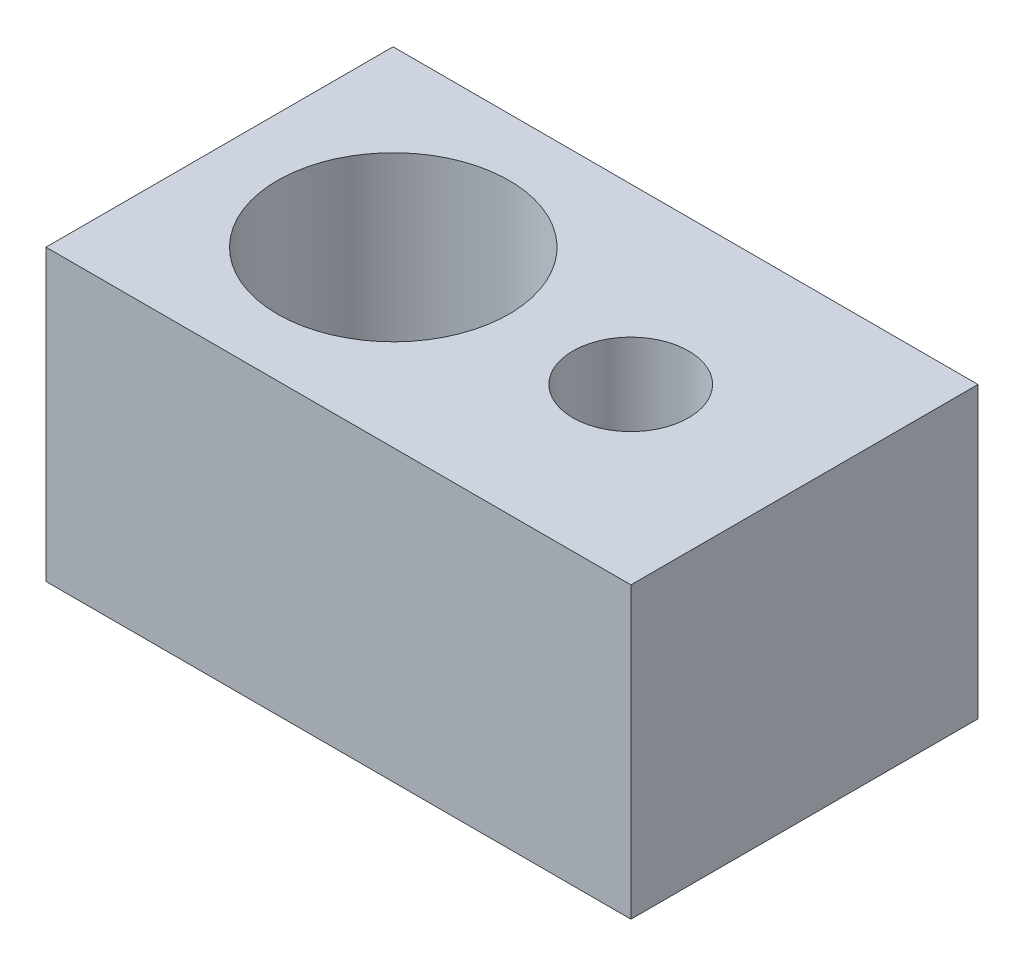
SolidWorks part; units mm, degrees
ref_plane "Front Plane" through (0, 0, 0) normal (0, 0, 1) x (1, 0, 0)
ref_plane "Top Plane" through (0, 0, 0) normal (0, 1, 0) x (1, 0, 0)
ref_plane "Right Plane" through (0, 0, 0) normal (1, 0, 0) x (0, 0, -1)
sketch "Sketch1" plane through (0, 0, 0) normal (0, 1, 0) x (1, 0, 0)
  line L0 (-50.5, 29.966) -> (9.5, 29.966) construction
  line L1 (-50.5, 29.966) -> (50.5, 29.966)
  line L2 (-50.5, 29.966) -> (-50.5, -29.966)
  line L3 (-50.5, -29.966) -> (50.5, -29.966)
  line L4 (50.5, 29.966) -> (50.5, -29.966)
  line L5 (-50.5, 29.966) -> (50.5, -29.966) construction
  line L6 (-50.5, -29.966) -> (50.5, 29.966) construction
  line L7 (9.5, 29.966) -> (9.5, -29.966) construction
  line L8 (-50.5, 29.966) -> (9.5, -29.966) construction
  line L9 (9.5, 29.966) -> (-50.5, -29.966) construction
  line L10 (-20.5, 0) -> (20.5, 0)
  circle A0 centre (-20.5, 0) radius 11
  circle A1 centre (20.5, 0) radius 10
  point P0 (0, 0)
  dimension "D1" = 22
  dimension "D3" = 20
  dimension "D4" = 30
  dimension "D5" = 41
  dimension "D2" = 60
extrude "Boss-Extrude1" add sketch "Sketch1" along normal blind 50
sketch "Sketch3" plane through (0, 0, 0) normal (0, -1, 0) x (1, 0, 0)
  circle A0 centre (-20.5, 0) radius 17
  dimension "D1" = 34
extrude "Cut-Extrude1" cut sketch "Sketch3" against normal blind 10
sketch "Sketch4" plane through (0, 50, 0) normal (0, 1, 0) x (1, 0, 0)
  circle A0 centre (-20.5, 0) radius 20
  dimension "D1" = 40
extrude "Cut-Extrude2" cut sketch "Sketch4" against normal blind 39
